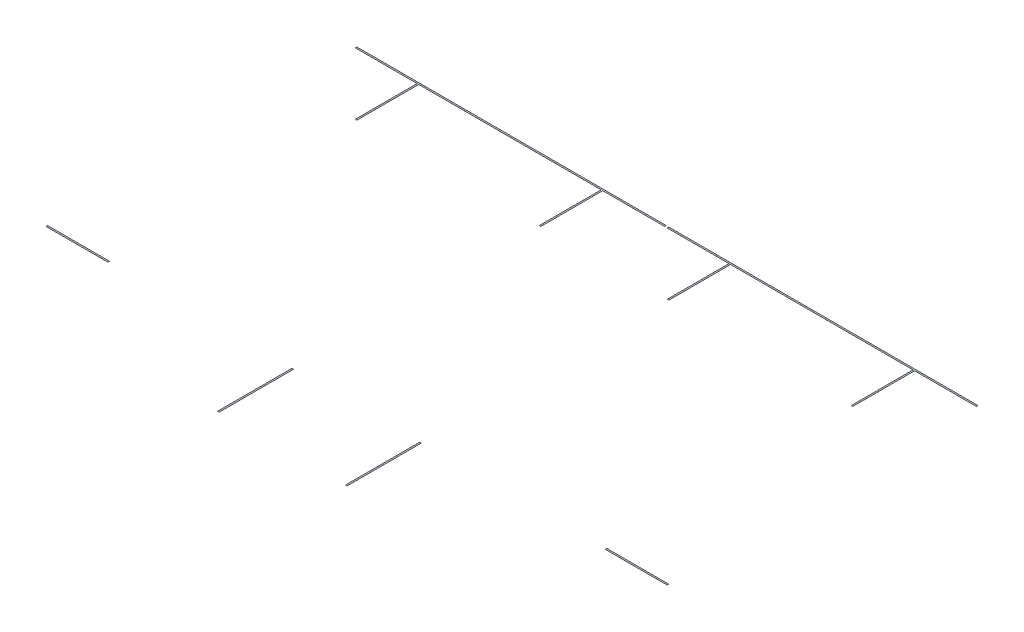
SolidWorks part; units mm, degrees
ref_plane "前视基准面" through (0, 0, 0) normal (0, 0, 1) x (1, 0, 0)
ref_plane "上视基准面" through (0, 0, 0) normal (0, 1, 0) x (1, 0, 0)
ref_plane "右视基准面" through (0, 0, 0) normal (1, 0, 0) x (0, 0, -1)
other "Configuration Table"
sketch "草图1" plane through (0, 0, 0) normal (0, 1, 0) x (1, 0, 0)
  line L0 (-6025, 0) -> (-25, 0)
  line L1 (-25, 0) -> (-25, -30)
  line L2 (-25, -30) -> (-1225, -30)
  line L3 (-1225, -30) -> (-1225, -1230)
  line L4 (-1225, -1230) -> (-1255, -1230)
  line L5 (-1255, -1230) -> (-1255, -30)
  line L6 (-1255, -30) -> (-4795, -30)
  line L7 (-4795, -30) -> (-4795, -1230)
  line L8 (-4795, -1230) -> (-4825, -1230)
  line L9 (-4825, -1230) -> (-4825, -30)
  line L10 (-4825, -30) -> (-6025, -30)
  line L11 (-6025, -30) -> (-6025, 0)
  line L12 (0, 0) -> (0, 116.7969) construction
  line L13 (-6025, -6000) -> (-4825, -6000)
  line L14 (-6025, -6000) -> (-6025, -6030)
  line L15 (-6025, -6030) -> (-4825, -6030)
  line L16 (-4825, -6000) -> (-4825, -6030)
  line L17 (-1255, -6030) -> (-1225, -6030)
  line L18 (-1255, -6030) -> (-1255, -7470)
  line L19 (-1255, -7470) -> (-1225, -7470)
  line L20 (-1225, -6030) -> (-1225, -7470)
  line L21 (6025, -6030) -> (4825, -6030)
  line L22 (4825, -6000) -> (4825, -6030)
  line L23 (6025, -6000) -> (4825, -6000)
  line L24 (6025, -6000) -> (6025, -6030)
  line L25 (1255, -7470) -> (1225, -7470)
  line L26 (1225, -6030) -> (1225, -7470)
  line L27 (1255, -6030) -> (1225, -6030)
  line L28 (1255, -6030) -> (1255, -7470)
  line L29 (4825, -30) -> (6025, -30)
  line L30 (4825, -1230) -> (4825, -30)
  line L31 (4795, -1230) -> (4825, -1230)
  line L32 (4795, -30) -> (4795, -1230)
  line L33 (1255, -30) -> (4795, -30)
  line L34 (1255, -1230) -> (1255, -30)
  line L35 (1225, -1230) -> (1255, -1230)
  line L36 (1225, -30) -> (1225, -1230)
  line L37 (25, -30) -> (1225, -30)
  line L38 (25, 0) -> (25, -30)
  line L39 (6025, 0) -> (25, 0)
  line L40 (6025, -30) -> (6025, 0)
  dimension "D1" = 25
  dimension "D2" = 6000
  dimension "D3" = 1200
  dimension "D4" = 4800
  dimension "D5" = 1440
  dimension "D6" = 30
  dimension "D7" = 1200
extrude "凸台-拉伸1" add sketch "草图1" along normal blind 0.2
